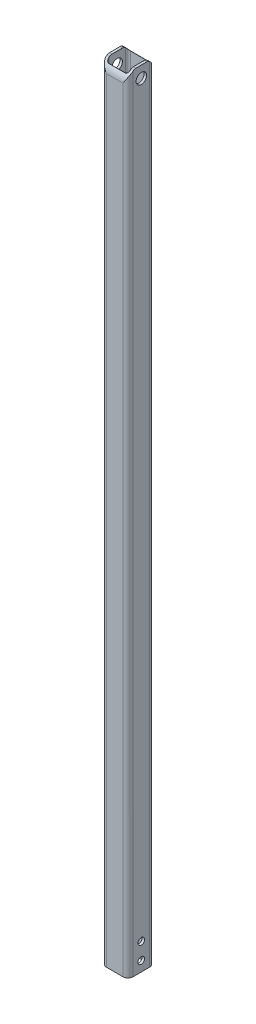
SolidWorks part; units mm, degrees
material "Plain Carbon Steel"
ref_plane "Front Plane" through (0, 0, 0) normal (0, 0, 1) x (1, 0, 0)
ref_plane "Top Plane" through (0, 0, 0) normal (0, 1, 0) x (1, 0, 0)
ref_plane "Right Plane" through (0, 0, 0) normal (1, 0, 0) x (0, 0, -1)
sketch3d "3DSketch1"
  line L0 (0, 0, 0) -> (0, 1500, 0)
  dimension "D1" = 1500
other "Tube (square) TS2X2X0.1875(2)"
ref_plane "Plane1" through (0, 0, 0) normal (0, 1, 0) x (1, 0, 0)
sketch "Sketch1" plane through (0, 0, 0) normal (0, 1, 0) x (1, 0, 0)
  line L0 (-15.875, -20.6375) -> (15.875, -20.6375)
  line L1 (-20.6375, -15.875) -> (-20.6375, 15.875)
  line L2 (15.875, 20.6375) -> (-15.875, 20.6375)
  line L3 (20.6375, 15.875) -> (20.6375, -15.875)
  line L4 (-15.875, -25.4) -> (15.875, -25.4)
  line L5 (-25.4, -15.875) -> (-25.4, 15.875)
  line L6 (15.875, 25.4) -> (-15.875, 25.4)
  line L7 (25.4, 15.875) -> (25.4, -15.875)
  line L8 (-25.4, 0) -> (-20.6375, 0) construction
  line L9 (-20.6375, 0) -> (20.6375, 0) construction
  line L10 (20.6375, 0) -> (25.4, 0) construction
  line L11 (0, 25.4) -> (0, 20.6375) construction
  line L12 (0, 20.6375) -> (0, -20.6375) construction
  line L13 (0, -20.6375) -> (0, -25.4) construction
  arc A0 (25.4, 15.875) -> (15.875, 25.4) centre (15.875, 15.875) ccw
  arc A1 (15.875, -25.4) -> (25.4, -15.875) centre (15.875, -15.875) ccw
  arc A2 (-25.4, -15.875) -> (-15.875, -25.4) centre (-15.875, -15.875) ccw
  arc A3 (-15.875, 25.4) -> (-25.4, 15.875) centre (-15.875, 15.875) ccw
  arc A4 (-15.875, 20.6375) -> (-20.6375, 15.875) centre (-15.875, 15.875) ccw
  arc A5 (20.6375, 15.875) -> (15.875, 20.6375) centre (15.875, 15.875) ccw
  arc A6 (15.875, -20.6375) -> (20.6375, -15.875) centre (15.875, -15.875) ccw
  arc A7 (-20.6375, -15.875) -> (-15.875, -20.6375) centre (-15.875, -15.875) ccw
  point P6 (-25.4, -25.4)
  point P33 (-25.4, 25.4)
  point P35 (25.4, 25.4)
  point P36 (25.4, -25.4)
  point P37 (0, 0)
  dimension "D1" = 9.525
  dimension "Thickness" = 4.7625
  dimension "V_leg" = 50.8
  dimension "H_leg" = 50.8
sketch "Sketch2" plane through (25.4, 0, 0) normal (1, 0, 0) x (0, 0, -1)
  line L0 (0, 1500) -> (0, 1477.775) construction
  line L1 (-15.875, 1500) -> (15.875, 1500) construction
  line L2 (-25.4, 1500) -> (-25.4, 0) construction
  line L3 (-25.4, 1477.775) -> (-25.4, 1500)
  line L4 (-25.4, 1500) -> (-12.2967, 1500)
  line L5 (25.4, 1500) -> (25.4, 1477.775)
  line L6 (20.6375, 1500) -> (15.875, 1500) construction
  line L7 (12.2967, 1500) -> (25.4, 1500)
  circle A0 centre (0, 1477.775) radius 10
  arc A1 (25.4, 1477.775) -> (12.2967, 1500) centre (0, 1477.775) ccw
  arc A2 (-12.2967, 1500) -> (-25.4, 1477.775) centre (0, 1477.775) ccw
  dimension "D1" = 20
  dimension "D2" = 22.225
extrude "Cut-Extrude1" cut sketch "Sketch2" against normal through all
fillet "Fillet1" radius 6.35 4 edges at (23.0188, 1500, -12.2967) (-23.0188, 1500, -12.2967) (23.0187, 1500, 12.2967) (-23.0188, 1500, 12.2967)
fillet "Fillet2" radius 0.127 16 edges at (-19.1342, 1494.232, -19.3476) (-20.6375, 1498.2928, -14.9727) (-20.6375, 1499.7297, -12.3634) (-20.6375, 1500, 0) (20.6375, 1498.2928, -14.9727) (20.6375, 1500, 0) (20.6375, 1499.7297, -12.3634) (18.0199, 1493.2688, -20.1271) (0, 1492.5822, -20.6375) (-20.6375, 1499.7297, 12.3634) (-20.6375, 1498.2928, 14.9727) (-18.0199, 1493.2688, 20.1271) (0, 1492.5822, 20.6375) (19.1342, 1494.232, 19.3476) (20.6375, 1498.2928, 14.9727) (20.6375, 1499.7297, 12.3634)
sketch "Sketch3" plane through (25.4, 0, 0) normal (1, 0, 0) x (0, 0, -1)
  line L0 (0, 0) -> (0, 50.8) construction
  line L1 (-15.875, 0) -> (15.875, 0) construction
  circle A0 centre (0, 50.8) radius 6.35
  circle A1 centre (0, 19.05) radius 6.35
  dimension "D3" = 12.7
  dimension "D1" = 19.05
  dimension "D2" = 50.8
extrude "Cut-Extrude2" cut sketch "Sketch3" against normal through all
equation "\"Arm_Length\" = 1.5m"
equation "\"D1@3DSketch1\"=\"Arm_Length\""
